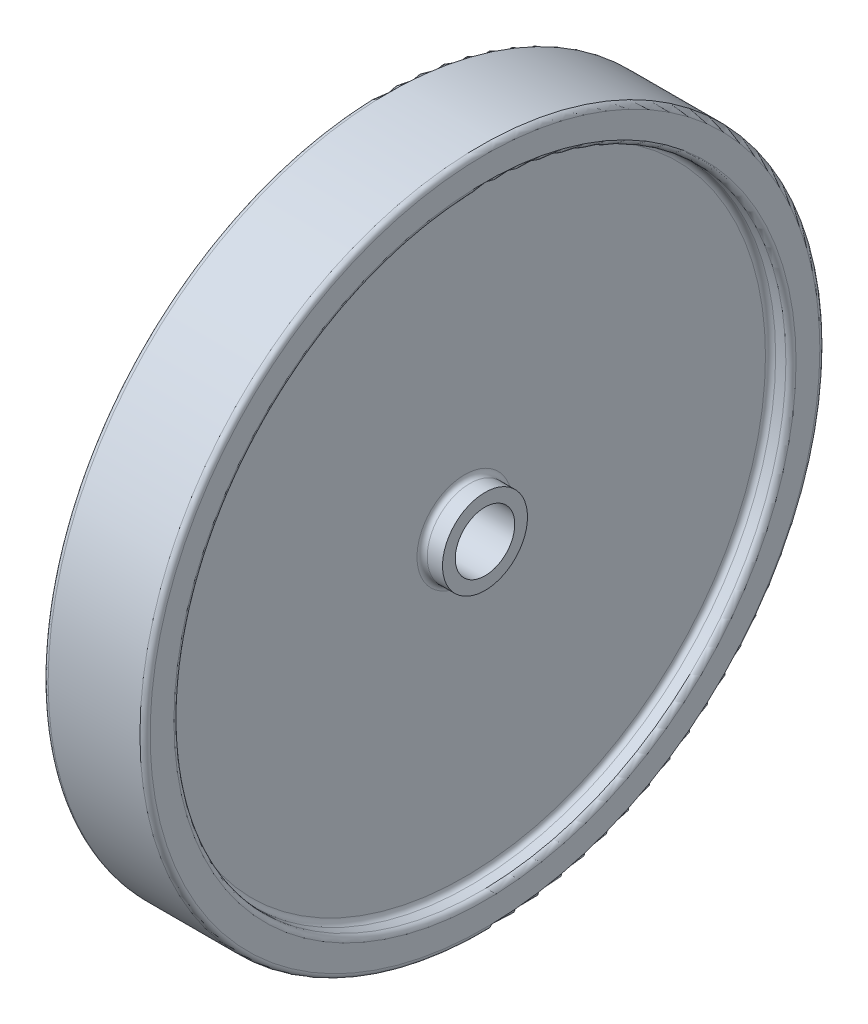
SolidWorks part; units mm, degrees
material "0.6015 (EN-GJL-150)"
ref_plane "Płaszczyzna przednia" through (0, 0, 0) normal (0, 0, 1) x (1, 0, 0)
ref_plane "Płaszczyzna górna" through (0, 0, 0) normal (0, 1, 0) x (1, 0, 0)
ref_plane "Płaszczyzna prawa" through (0, 0, 0) normal (1, 0, 0) x (0, 0, -1)
sketch "Szkic1" plane through (0, 0, 0) normal (1, 0, 0) x (0, 0, -1)
  circle A0 centre (0, 0) radius 200
  circle A1 centre (0, 0) radius 17.5
  dimension "D1" = 400
  dimension "D2" = 35
extrude "Dodanie-wyciągnięcie1" add sketch "Szkic1" along normal blind 60
fillet "Zaokrąglenie1" radius 3 2 edges at (0, 0, -200) (60, 0, -200)
sketch "Szkic2" plane through (60, 0, 0) normal (1, 0, 0) x (0, 0, -1)
  circle A0 centre (0, 0) radius 25
  circle A1 centre (0, 0) radius 180
  dimension "D1" = 50
  dimension "D2" = 360
extrude "Wytnij-wyciągnięcie1" cut sketch "Szkic2" against normal blind 12
fillet "Zaokrąglenie2" radius 3 3 edges at (48, 0, -25) (48, 0, -180) (60, 0, -180)
ref_plane "Płaszczyzna1" through (30, 0, 0) normal (1, 0, 0) x (0, 0, -1)
mirror "Lustro1" about plane through (30, 0, 0) normal (1, 0, 0) of "Wytnij-wyciągnięcie1"
fillet "Zaokrąglenie3" radius 3 3 edges at (0, 0, -180) (12, 0, -180) (12, 0, -25)
